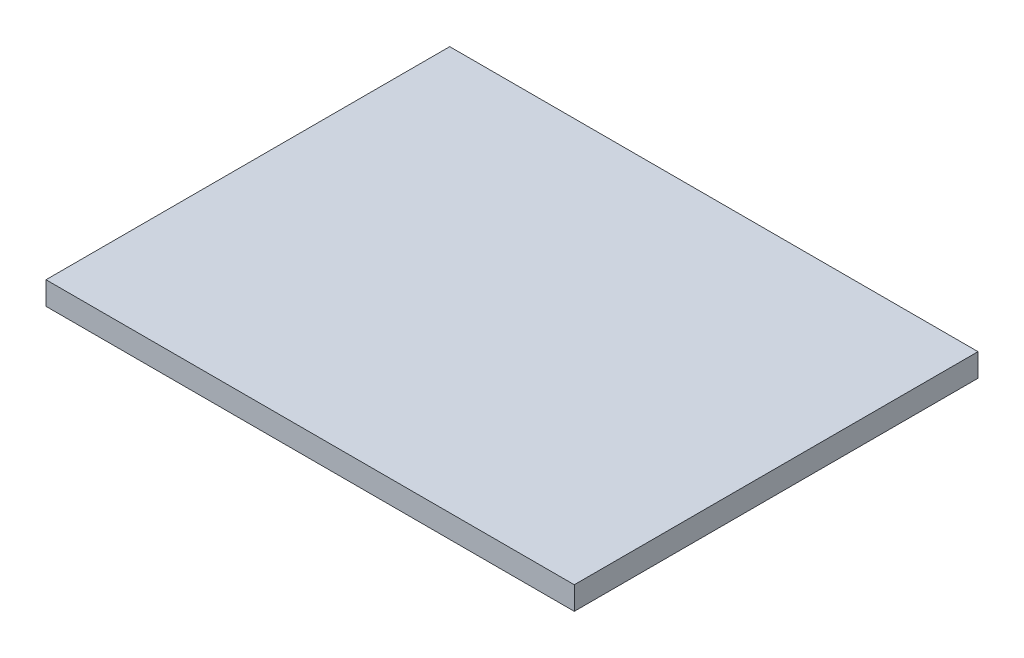
SolidWorks part; units mm, degrees
ref_plane "Front Plane" through (0, 0, 0) normal (0, 0, 1) x (1, 0, 0)
ref_plane "Top Plane" through (0, 0, 0) normal (0, 1, 0) x (1, 0, 0)
ref_plane "Right Plane" through (0, 0, 0) normal (1, 0, 0) x (0, 0, -1)
sketch "Sketch1" plane through (0, 0, 0) normal (0, 1, 0) x (1, 0, 0)
  line L1 (0, 0) -> (229, 0)
  line L2 (0, 0) -> (0, 175)
  line L3 (0, 175) -> (229, 175)
  line L4 (229, 0) -> (229, 175)
  dimension "D1" = 229
  dimension "D2" = 175
extrude "Boss-Extrude1" add sketch "Sketch1" along normal blind 10
